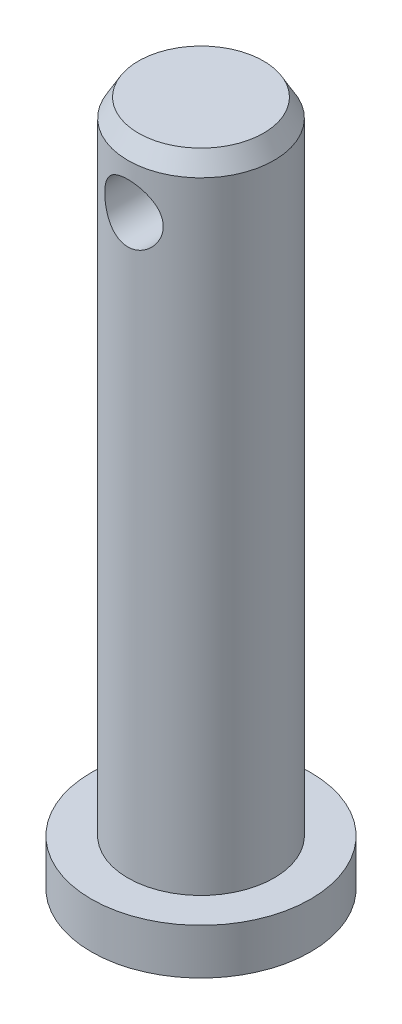
SolidWorks part; units mm, degrees
material "AISI 304"
ref_plane "前视基准面" through (0, 0, 0) normal (0, 0, 1) x (1, 0, 0)
ref_plane "上视基准面" through (0, 0, 0) normal (0, 1, 0) x (1, 0, 0)
ref_plane "右视基准面" through (0, 0, 0) normal (1, 0, 0) x (0, 0, -1)
sketch "草图1" plane through (0, 0, 0) normal (0, 0, 1) x (1, 0, 0)
  line L0 (0, 0) -> (6, 0)
  line L1 (6, 0) -> (6, 2.5)
  line L2 (6, 2.5) -> (4, 2.5)
  line L3 (4, 2.5) -> (4, 36.5)
  line L4 (3.4226, 37.5) -> (0, 37.5)
  line L5 (0, 37.5) -> (0, 0)
  line L6 (0, 0) -> (0, -14400.4222) construction
  line L7 (3.4226, 37.5) -> (4, 36.5)
  dimension "D1" = 30
  dimension "D" = 8
  dimension "D2" = 1
  dimension "Dk" = 12
  dimension "k" = 2.5
  dimension "L" = 35
revolve "旋转1" add sketch "草图1" angle 360 about L6
sketch "草图2" plane through (0, 0, 0) normal (0, 0, 1) x (1, 0, 0)
  line L0 (4, 37.5) -> (-4, 37.5) construction
  circle A0 centre (0, 34) radius 1.6
  dimension "D1" = 3.2
  dimension "lc" = 3.5
extrude "切除-拉伸1" cut sketch "草图2" against normal through all both and the other way through all
